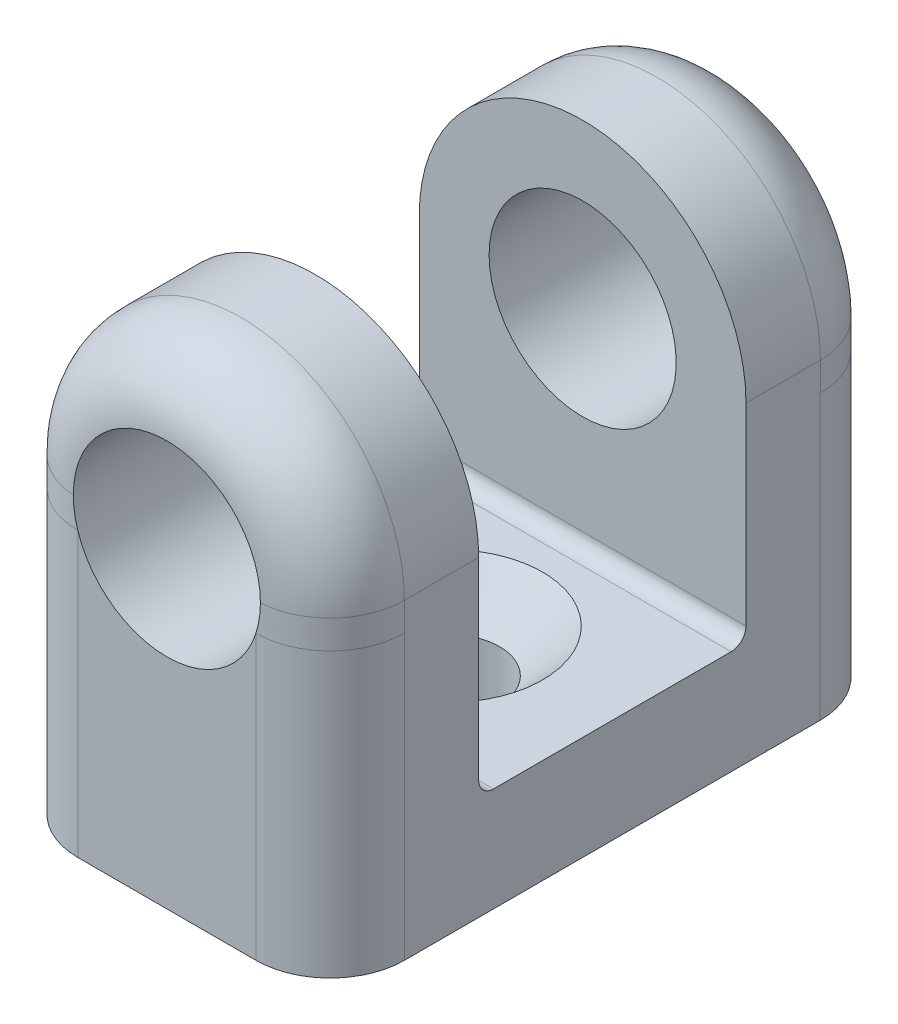
SolidWorks part; units mm, degrees
ref_plane "Plan de face" through (0, 0, 0) normal (0, 0, 1) x (1, 0, 0)
ref_plane "Plan de dessus" through (0, 0, 0) normal (0, 1, 0) x (1, 0, 0)
ref_plane "Plan de droite" through (0, 0, 0) normal (1, 0, 0) x (0, 0, -1)
sketch "Esquisse1" plane through (0, 0, 0) normal (0, 0, 1) x (1, 0, 0)
  line L0 (0, 0) -> (0, 20) construction
  line L1 (-12.6705, 0) -> (14.6714, 0) construction
  line L2 (-12.6705, 14) -> (14.6714, 14) construction
  line L4 (-5.5, 3.5) -> (-5.5, 14)
  line L5 (5.5, 3.5) -> (5.5, 14)
  line L6 (0, 8.5) -> (-5.5, 8.5) construction
  line L7 (-5.5, 3.5) -> (5.5, 3.5) construction
  line L8 (-5.5, 3.5) -> (5.5, 3.5)
  circle A0 centre (0, 14) radius 3.15
  arc A1 (-5.5, 14) -> (5.5, 14) centre (0, 14) cw
  circle A2 centre (0, 14) radius 5.5 construction
  dimension "D2" = 5
  dimension "D1" = 14
extrude "Boss.-Extru.1" add sketch "Esquisse1" along normal blind 19
sketch "Esquisse2" plane through (5.5, 0, 0) normal (1, 0, 0) x (0, 0, -1)
  line L0 (-9.5, 0) -> (-9.5, 19.5) construction
  line L2 (0, 19.5) -> (-19, 19.5) construction
  line L3 (-14, 7) -> (-5, 7)
  line L4 (-14, 7) -> (-14, 19.5)
  line L5 (-14, 19.5) -> (-5, 19.5)
  line L6 (-5, 7) -> (-5, 19.5)
  line L7 (-19, 3.5) -> (0, 3.5) construction
  point P11 (-9.5, 4)
  dimension "D1" = 3.5
extrude "Enlèv. mat.-Extru.1" cut sketch "Esquisse2" against normal blind 15
sketch "Esquisse3" plane through (0, 7, 0) normal (0, 1, 0) x (1, 0, 0)
  line L0 (-5.5, -9.5) -> (5.5, -9.5) construction
  line L1 (-5.5, -14) -> (-5.5, -5) construction
  line L2 (5.5, -14) -> (5.5, -5) construction
  point P6 (0, -9.5)
hole_wizard "Fraisage pour vis à tête fraisée M31" positions "Esquisse5" profile "Esquisse4" countersink size "M3" standard "Iso" end condition through all
sketch "Esquisse5" plane through (0, 7, 0) normal (0, 1, 0) x (1, 0, 0)
  point P0 (0, -9.5)
sketch "Esquisse4" plane through (0, 7, 9.5) normal (1, 0, 0) x (0, 0, 1)
  line L0 (0, 0) -> (0, 3.5)
  line L1 (0, 3.5) -> (1.7, 3.5)
  line L2 (1.7, 3.5) -> (1.7, 1.45)
  line L3 (1.7, 1.45) -> (3.15, 0)
  line L5 (3.15, 0) -> (0, 0)
  line L6 (-1.7, 1.45) -> (-3.15, 0) construction
  line L11 (0, -6.35) -> (0, 107.95) construction
  dimension "Diamètre du perçage jusqu'au prochain" = 3.4
  dimension "Profondeur du perçage jusqu'au prochain" = 3.5
  dimension "Diamètre du fraisage entrant" = 6.3
  dimension "Angle du fraisage entrant" = 90
fillet "Congé1" radius 2.5 4 edges at (5.5, 8.75, 0) (5.5, 8.75, 19) (-5.5, 8.75, 19) (-5.5, 8.75, 0)
fillet "Congé2" radius 0.5 2 edges at (0, 7, 5) (0, 7, 14)
ref_plane "Plan1" through (0, 13, 0) normal (0, 1, 0) x (1, 0, 0)
